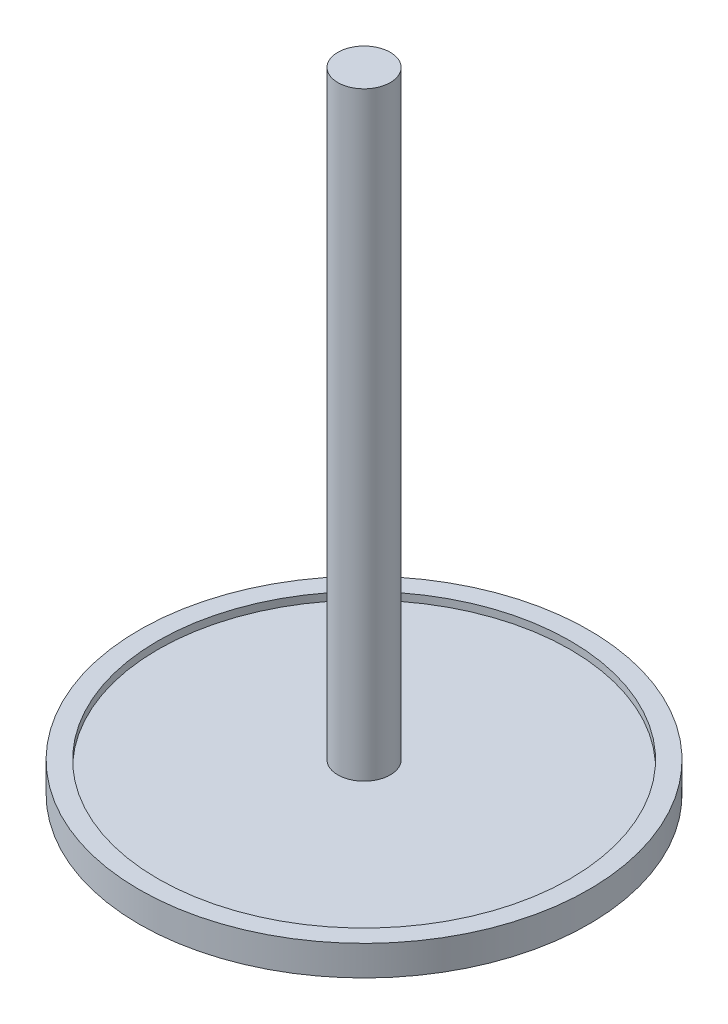
SolidWorks part; units mm, degrees
ref_plane "Front Plane" through (0, 0, 0) normal (0, 0, 1) x (1, 0, 0)
ref_plane "Top Plane" through (0, 0, 0) normal (0, 1, 0) x (1, 0, 0)
ref_plane "Right Plane" through (0, 0, 0) normal (1, 0, 0) x (0, 0, -1)
sketch "Sketch1" plane through (0, 0, 0) normal (0, 1, 0) x (1, 0, 0)
  circle A0 centre (0, 0) radius 150
  dimension "D1" = 300
extrude "Boss-Extrude1" add sketch "Sketch1" along normal blind 20
sketch "Sketch2" plane through (0, 20, 0) normal (0, 1, 0) x (1, 0, 0)
  circle A0 centre (0, 0) radius 17.5
  dimension "D1" = 35
extrude "Boss-Extrude2" add sketch "Sketch2" along normal blind 400
sketch "Sketch4" plane through (0, 20, 0) normal (0, 1, 0) x (1, 0, 0)
  circle A0 centre (0, 0) radius 137.5
  dimension "D1" = 275
extrude "Cut-Extrude1" cut sketch "Sketch4" against normal blind 5
